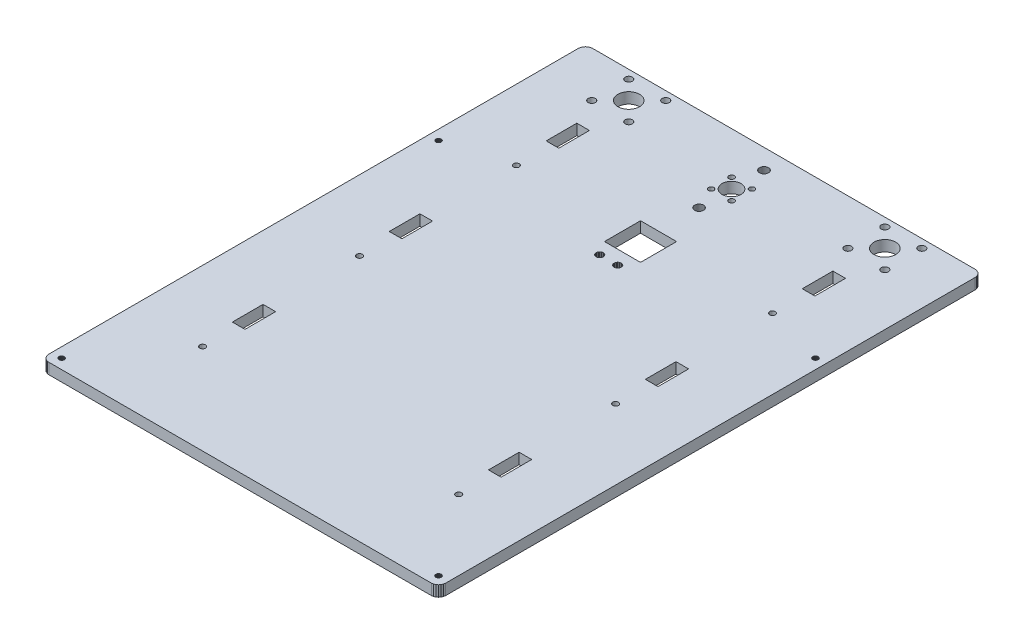
SolidWorks part; units mm, degrees
ref_plane "Alzado" through (0, 0, 0) normal (0, 0, 1) x (1, 0, 0)
ref_plane "Planta" through (0, 0, 0) normal (0, 1, 0) x (1, 0, 0)
ref_plane "Vista lateral" through (0, 0, 0) normal (1, 0, 0) x (0, 0, -1)
sketch "Croquis1" plane through (0, 0, 0) normal (0, 1, 0) x (1, 0, 0)
  line L0 (-2.4786, 139.4098) -> (-2.5, 139.7361)
  line L1 (-2.4148, 139.0891) -> (-2.4786, 139.4098)
  line L2 (-2.3097, 138.7794) -> (-2.4148, 139.0891)
  line L3 (-2.1651, 138.4861) -> (-2.3097, 138.7794)
  line L4 (-1.9834, 138.2142) -> (-2.1651, 138.4861)
  line L5 (-1.7678, 137.9684) -> (-1.9834, 138.2142)
  line L6 (-1.5219, 137.7528) -> (-1.7678, 137.9684)
  line L7 (-1.25, 137.5711) -> (-1.5219, 137.7528)
  line L8 (-0.9567, 137.4264) -> (-1.25, 137.5711)
  line L9 (-0.647, 137.3213) -> (-0.9567, 137.4264)
  line L10 (-0.3263, 137.2575) -> (-0.647, 137.3213)
  line L11 (0, 137.2361) -> (-0.3263, 137.2575)
  line L12 (0.3263, 137.2575) -> (0, 137.2361)
  line L13 (0.647, 137.3213) -> (0.3263, 137.2575)
  line L14 (0.9567, 137.4264) -> (0.647, 137.3213)
  line L15 (1.25, 137.5711) -> (0.9567, 137.4264)
  line L16 (1.5219, 137.7528) -> (1.25, 137.5711)
  line L17 (1.7678, 137.9684) -> (1.5219, 137.7528)
  line L18 (1.9834, 138.2142) -> (1.7678, 137.9684)
  line L19 (2.1651, 138.4861) -> (1.9834, 138.2142)
  line L20 (2.3097, 138.7794) -> (2.1651, 138.4861)
  line L21 (2.4148, 139.0891) -> (2.3097, 138.7794)
  line L22 (2.4786, 139.4098) -> (2.4148, 139.0891)
  line L23 (2.5, 139.7361) -> (2.4786, 139.4098)
  line L24 (-2.4148, 103.0891) -> (-2.4786, 103.4098)
  line L25 (-2.3097, 102.7794) -> (-2.4148, 103.0891)
  line L26 (-2.1651, 102.4861) -> (-2.3097, 102.7794)
  line L27 (-9, 81.2639) -> (9, 81.2639)
  line L28 (-2.4786, 103.4098) -> (-2.5, 103.7361)
  line L29 (-1.9834, 102.2142) -> (-2.1651, 102.4861)
  line L30 (-1.7678, 101.9684) -> (-1.9834, 102.2142)
  line L31 (-1.5219, 101.7528) -> (-1.7678, 101.9684)
  line L32 (-1.25, 101.5711) -> (-1.5219, 101.7528)
  line L33 (-0.9567, 101.4264) -> (-1.25, 101.5711)
  line L34 (-0.647, 101.3213) -> (-0.9567, 101.4264)
  line L35 (-0.3263, 101.2575) -> (-0.647, 101.3213)
  line L36 (0, 101.2361) -> (-0.3263, 101.2575)
  line L37 (0.3263, 101.2575) -> (0, 101.2361)
  line L38 (0.647, 101.3213) -> (0.3263, 101.2575)
  line L39 (0.9567, 101.4264) -> (0.647, 101.3213)
  line L40 (1.25, 101.5711) -> (0.9567, 101.4264)
  line L41 (1.5219, 101.7528) -> (1.25, 101.5711)
  line L42 (1.7678, 101.9684) -> (1.5219, 101.7528)
  line L43 (1.9834, 102.2142) -> (1.7678, 101.9684)
  line L44 (2.1651, 102.4861) -> (1.9834, 102.2142)
  line L45 (2.3097, 102.7794) -> (2.1651, 102.4861)
  line L46 (2.4148, 103.0891) -> (2.3097, 102.7794)
  line L47 (2.4786, 103.4098) -> (2.4148, 103.0891)
  line L48 (2.5, 103.7361) -> (2.4786, 103.4098)
  line L50 (3.0681, 53.0893) -> (3, 53.6069)
  line L51 (3.2679, 52.6069) -> (3.0681, 53.0893)
  line L52 (3.5858, 52.1927) -> (3.2679, 52.6069)
  line L53 (4, 51.8749) -> (3.5858, 52.1927)
  line L54 (4.4824, 51.6751) -> (4, 51.8749)
  line L55 (5, 51.6069) -> (4.4824, 51.6751)
  line L56 (5.5176, 51.6751) -> (5, 51.6069)
  line L58 (6, 51.8749) -> (5.5176, 51.6751)
  line L59 (6.4142, 52.1927) -> (6, 51.8749)
  line L60 (6.7321, 52.6069) -> (6.4142, 52.1927)
  line L61 (6.9319, 53.0893) -> (6.7321, 52.6069)
  line L62 (7, 53.6069) -> (6.9319, 53.0893)
  line L63 (-105.9489, -145.6244) -> (-106, -145.2361)
  line L64 (-105.799, -145.9861) -> (-105.9489, -145.6244)
  line L65 (-105.5607, -146.2968) -> (-105.799, -145.9861)
  line L66 (-105.25, -146.5352) -> (-105.5607, -146.2968)
  line L67 (-104.8882, -146.685) -> (-105.25, -146.5352)
  line L68 (-104.5, -146.7361) -> (-104.8882, -146.685)
  line L69 (-106, -150.7361) -> (106, -150.7361)
  line L70 (-104.1118, -146.685) -> (-104.5, -146.7361)
  line L71 (-103.75, -146.5352) -> (-104.1118, -146.685)
  line L72 (-103.4393, -146.2968) -> (-103.75, -146.5352)
  line L73 (-103.201, -145.9861) -> (-103.4393, -146.2968)
  line L74 (-103.0511, -145.6244) -> (-103.201, -145.9861)
  line L75 (-103, -145.2361) -> (-103.0511, -145.6244)
  line L77 (60.747, 148.0892) -> (60.747, 143.8892) construction
  line L78 (-71, 135.7361) -> (-71, -150.7361) construction
  line L79 (71, 135.7361) -> (71, -150.7361) construction
  line L80 (-74.5, 23.4409) -> (-67.5, 23.4409)
  line L81 (-74.5, 110.4409) -> (-67.5, 110.4409)
  line L82 (-74.5, 110.4409) -> (-74.5, 93.4409)
  line L83 (-74.5, 93.4409) -> (-67.5, 93.4409)
  line L84 (-67.5, 110.4409) -> (-67.5, 93.4409)
  line L85 (-74.5, 110.4409) -> (-67.5, 93.4409) construction
  line L86 (-74.5, 93.4409) -> (-67.5, 110.4409) construction
  line L87 (-74.5, 23.4409) -> (-74.5, 6.4409)
  line L88 (-74.5, 6.4409) -> (-67.5, 6.4409)
  line L89 (-67.5, 23.4409) -> (-67.5, 6.4409)
  line L90 (-74.5, 23.4409) -> (-67.5, 6.4409) construction
  line L91 (-74.5, 6.4409) -> (-67.5, 23.4409) construction
  line L92 (-74.5, -63.5591) -> (-67.5, -63.5591)
  line L93 (-74.5, -63.5591) -> (-74.5, -80.5591)
  line L94 (-74.5, -80.5591) -> (-67.5, -80.5591)
  line L95 (-67.5, -63.5591) -> (-67.5, -80.5591)
  line L96 (-74.5, -63.5591) -> (-67.5, -80.5591) construction
  line L97 (-74.5, -80.5591) -> (-67.5, -63.5591) construction
  line L98 (0, 121.7361) -> (0, -150.7361) construction
  line L100 (74.5, -80.5591) -> (67.5, -63.5591) construction
  line L101 (74.5, -63.5591) -> (67.5, -80.5591) construction
  line L102 (74.5, 6.4409) -> (67.5, 23.4409) construction
  line L103 (74.5, 23.4409) -> (67.5, 6.4409) construction
  line L104 (74.5, 93.4409) -> (67.5, 110.4409) construction
  line L105 (74.5, 110.4409) -> (67.5, 93.4409) construction
  line L106 (67.5, -63.5591) -> (67.5, -80.5591)
  line L107 (74.5, -80.5591) -> (67.5, -80.5591)
  line L108 (74.5, -63.5591) -> (74.5, -80.5591)
  line L109 (74.5, -63.5591) -> (67.5, -63.5591)
  line L110 (67.5, 23.4409) -> (67.5, 6.4409)
  line L111 (74.5, 6.4409) -> (67.5, 6.4409)
  line L112 (74.5, 23.4409) -> (74.5, 6.4409)
  line L113 (67.5, 110.4409) -> (67.5, 93.4409)
  line L114 (74.5, 93.4409) -> (67.5, 93.4409)
  line L115 (74.5, 110.4409) -> (74.5, 93.4409)
  line L116 (74.5, 110.4409) -> (67.5, 110.4409)
  line L117 (74.5, 23.4409) -> (67.5, 23.4409)
  line L150 (10, 62.2639) -> (10, 61.2639)
  line L151 (103.201, -145.9861) -> (103.0511, -145.6244)
  line L152 (10, 80.2639) -> (10, 62.2639)
  line L189 (103.0511, -145.6244) -> (103, -145.2361)
  line L244 (103.4393, -146.2968) -> (103.201, -145.9861)
  line L245 (103.75, -146.5352) -> (103.4393, -146.2968)
  line L246 (104.1118, -146.685) -> (103.75, -146.5352)
  line L247 (104.5, -146.7361) -> (104.1118, -146.685)
  line L248 (104.8882, -146.685) -> (104.5, -146.7361)
  line L249 (105.25, -146.5352) -> (104.8882, -146.685)
  line L250 (105.5607, -146.2968) -> (105.25, -146.5352)
  line L251 (105.799, -145.9861) -> (105.5607, -146.2968)
  line L252 (105.9489, -145.6244) -> (105.799, -145.9861)
  line L253 (106, -145.2361) -> (105.9489, -145.6244)
  line L254 (106, -150.7361) -> (107.0353, -150.5998)
  line L255 (107.0353, 150.5998) -> (106, 150.7361)
  line L256 (107.0353, -150.5998) -> (108, -150.2002)
  line L257 (108, 150.2002) -> (107.0353, 150.5998)
  line L258 (108, -150.2002) -> (108.8284, -149.5646)
  line L259 (108.8284, 149.5646) -> (108, 150.2002)
  line L260 (108.8284, -149.5646) -> (109.4641, -148.7361)
  line L261 (109.4641, 148.7361) -> (108.8284, 149.5646)
  line L262 (109.4641, -148.7361) -> (109.8637, -147.7714)
  line L263 (109.8637, 147.7714) -> (109.4641, 148.7361)
  line L264 (109.8637, -147.7714) -> (110, -146.7361)
  line L265 (110, -146.7361) -> (110, 146.7361)
  line L266 (110, 146.7361) -> (109.8637, 147.7714)
  line L267 (-110, 146.7361) -> (-110, -146.7361)
  line L268 (-110, -146.7361) -> (-109.8637, -147.7714)
  line L269 (-109.8637, 147.7714) -> (-110, 146.7361)
  line L270 (-109.8637, -147.7714) -> (-109.4641, -148.7361)
  line L271 (-109.4641, 148.7361) -> (-109.8637, 147.7714)
  line L272 (-109.4641, -148.7361) -> (-108.8284, -149.5646)
  line L273 (-108.8284, 149.5646) -> (-109.4641, 148.7361)
  line L274 (-108.8284, -149.5646) -> (-108, -150.2002)
  line L275 (-108, 150.2002) -> (-108.8284, 149.5646)
  line L276 (-108, -150.2002) -> (-107.0353, -150.5998)
  line L277 (-107.0353, 150.5998) -> (-108, 150.2002)
  line L278 (-107.0353, -150.5998) -> (-106, -150.7361)
  line L279 (-106, 150.7361) -> (-107.0353, 150.5998)
  line L280 (-106, 63.7639) -> (-105.9489, 64.1521)
  line L291 (106, 150.7361) -> (-106, 150.7361)
  line L292 (-105.9489, 64.1521) -> (-105.799, 64.5139)
  line L293 (-105.799, 64.5139) -> (-105.5607, 64.8245)
  line L294 (-105.5607, 64.8245) -> (-105.25, 65.0629)
  line L295 (-105.25, 65.0629) -> (-104.8882, 65.2128)
  line L296 (-104.8882, 65.2128) -> (-104.5, 65.2639)
  line L297 (-104.5, 65.2639) -> (-104.1118, 65.2128)
  line L298 (-104.1118, 65.2128) -> (-103.75, 65.0629)
  line L299 (-103.75, 65.0629) -> (-103.4393, 64.8245)
  line L300 (-103.4393, 64.8245) -> (-103.201, 64.5139)
  line L301 (-103.201, 64.5139) -> (-103.0511, 64.1521)
  line L302 (-103.0511, 64.1521) -> (-103, 63.7639)
  line L358 (-0.647, 142.151) -> (-0.3263, 142.2147)
  line L359 (-0.9567, 142.0458) -> (-0.647, 142.151)
  line L360 (-1.25, 141.9012) -> (-0.9567, 142.0458)
  line L361 (-1.5219, 141.7195) -> (-1.25, 141.9012)
  line L362 (-1.7678, 141.5039) -> (-1.5219, 141.7195)
  line L363 (-1.9834, 141.258) -> (-1.7678, 141.5039)
  line L364 (-2.1651, 140.9861) -> (-1.9834, 141.258)
  line L365 (-2.3097, 140.6928) -> (-2.1651, 140.9861)
  line L366 (-2.4148, 140.3832) -> (-2.3097, 140.6928)
  line L367 (-2.4786, 140.0625) -> (-2.4148, 140.3832)
  line L368 (-10, 61.2639) -> (-10, 62.2639)
  line L369 (-10, 81.2639) -> (-9, 81.2639)
  line L370 (-2.5, 139.7361) -> (-2.4786, 140.0625)
  line L371 (-0.3263, 142.2147) -> (0, 142.2361)
  line L372 (0, 142.2361) -> (0.3263, 142.2147)
  line L373 (0.3263, 142.2147) -> (0.647, 142.151)
  line L374 (0.647, 142.151) -> (0.9567, 142.0458)
  line L375 (0.9567, 142.0458) -> (1.25, 141.9012)
  line L376 (1.25, 141.9012) -> (1.5219, 141.7195)
  line L377 (1.5219, 141.7195) -> (1.7678, 141.5039)
  line L378 (1.7678, 141.5039) -> (1.9834, 141.258)
  line L379 (1.9834, 141.258) -> (2.1651, 140.9861)
  line L380 (2.1651, 140.9861) -> (2.3097, 140.6928)
  line L381 (2.3097, 140.6928) -> (2.4148, 140.3832)
  line L382 (2.4148, 140.3832) -> (2.4786, 140.0625)
  line L383 (2.4786, 140.0625) -> (2.5, 139.7361)
  line L386 (9, 81.2639) -> (10, 81.2639)
  line L387 (10, 81.2639) -> (10, 80.2639)
  line L476 (103, 63.7639) -> (103.0511, 64.1521)
  line L477 (103.0511, 64.1521) -> (103.201, 64.5139)
  line L478 (103.201, 64.5139) -> (103.4393, 64.8245)
  line L479 (103.4393, 64.8245) -> (103.75, 65.0629)
  line L480 (103.75, 65.0629) -> (104.1118, 65.2128)
  line L481 (104.1118, 65.2128) -> (104.5, 65.2639)
  line L482 (104.5, 65.2639) -> (104.8882, 65.2128)
  line L483 (104.8882, 65.2128) -> (105.25, 65.0629)
  line L484 (105.25, 65.0629) -> (105.5607, 64.8245)
  line L485 (105.5607, 64.8245) -> (105.799, 64.5139)
  line L486 (105.799, 64.5139) -> (105.9489, 64.1521)
  line L487 (105.9489, 64.1521) -> (106, 63.7639)
  line L488 (103, -145.2361) -> (103.0511, -144.8479)
  line L489 (103.0511, 63.3756) -> (103, 63.7639)
  line L490 (103.0511, -144.8479) -> (103.201, -144.4861)
  line L491 (103.201, 63.0139) -> (103.0511, 63.3756)
  line L492 (103.201, -144.4861) -> (103.4393, -144.1755)
  line L493 (103.4393, 62.7032) -> (103.201, 63.0139)
  line L494 (103.4393, -144.1755) -> (103.75, -143.9371)
  line L495 (103.75, 62.4648) -> (103.4393, 62.7032)
  line L496 (103.75, -143.9371) -> (104.1118, -143.7872)
  line L497 (104.1118, 62.315) -> (103.75, 62.4648)
  line L498 (104.1118, -143.7872) -> (104.5, -143.7361)
  line L499 (104.5, 62.2639) -> (104.1118, 62.315)
  line L500 (104.5, -143.7361) -> (104.8882, -143.7872)
  line L501 (104.8882, 62.315) -> (104.5, 62.2639)
  line L502 (104.8882, -143.7872) -> (105.25, -143.9371)
  line L503 (105.25, 62.4648) -> (104.8882, 62.315)
  line L504 (105.25, -143.9371) -> (105.5607, -144.1755)
  line L505 (105.5607, 62.7032) -> (105.25, 62.4648)
  line L506 (105.5607, -144.1755) -> (105.799, -144.4861)
  line L507 (105.799, 63.0139) -> (105.5607, 62.7032)
  line L508 (105.799, -144.4861) -> (105.9489, -144.8479)
  line L509 (105.9489, 63.3756) -> (105.799, 63.0139)
  line L510 (105.9489, -144.8479) -> (106, -145.2361)
  line L511 (106, 63.7639) -> (105.9489, 63.3756)
  line L622 (-9, 61.2639) -> (-10, 61.2639)
  line L624 (-7, 53.6069) -> (-6.9319, 54.1246)
  line L625 (-6.9319, 54.1246) -> (-6.7321, 54.6069)
  line L626 (-6.7321, 54.6069) -> (-6.4142, 55.0211)
  line L627 (-6.4142, 55.0211) -> (-6, 55.339)
  line L628 (-6, 55.339) -> (-5.5176, 55.5388)
  line L629 (9, 61.2639) -> (-9, 61.2639)
  line L631 (-5.5176, 55.5388) -> (-5, 55.6069)
  line L632 (-5, 55.6069) -> (-4.4824, 55.5388)
  line L633 (-4.4824, 55.5388) -> (-4, 55.339)
  line L634 (-4, 55.339) -> (-3.5858, 55.0211)
  line L635 (-3.5858, 55.0211) -> (-3.2679, 54.6069)
  line L636 (-3.2679, 54.6069) -> (-3.0681, 54.1246)
  line L637 (-3.0681, 54.1246) -> (-3, 53.6069)
  line L638 (3.2679, 54.6069) -> (3.5858, 55.0211)
  line L639 (3.0681, 54.1246) -> (3.2679, 54.6069)
  line L640 (3, 53.6069) -> (3.0681, 54.1246)
  line L643 (3.5858, 55.0211) -> (4, 55.339)
  line L644 (4, 55.339) -> (4.4824, 55.5388)
  line L645 (4.4824, 55.5388) -> (5, 55.6069)
  line L646 (5, 55.6069) -> (5.5176, 55.5388)
  line L647 (5.5176, 55.5388) -> (6, 55.339)
  line L648 (6, 55.339) -> (6.4142, 55.0211)
  line L649 (6.4142, 55.0211) -> (6.7321, 54.6069)
  line L650 (6.7321, 54.6069) -> (6.9319, 54.1246)
  line L651 (6.9319, 54.1246) -> (7, 53.6069)
  line L654 (10, 61.2639) -> (9, 61.2639)
  line L656 (-2.5, 103.7361) -> (-2.4786, 104.0625)
  line L657 (-2.4786, 104.0625) -> (-2.4148, 104.3832)
  line L658 (-2.4148, 104.3832) -> (-2.3097, 104.6928)
  line L659 (-2.3097, 104.6928) -> (-2.1651, 104.9861)
  line L660 (-2.1651, 104.9861) -> (-1.9834, 105.258)
  line L661 (-1.9834, 105.258) -> (-1.7678, 105.5039)
  line L662 (-1.7678, 105.5039) -> (-1.5219, 105.7195)
  line L663 (-1.5219, 105.7195) -> (-1.25, 105.9012)
  line L664 (-1.25, 105.9012) -> (-0.9567, 106.0458)
  line L665 (-0.9567, 106.0458) -> (-0.647, 106.151)
  line L666 (-0.647, 106.151) -> (-0.3263, 106.2147)
  line L667 (-0.3263, 106.2147) -> (0, 106.2361)
  line L668 (0, 106.2361) -> (0.3263, 106.2147)
  line L669 (0.3263, 106.2147) -> (0.647, 106.151)
  line L670 (0.647, 106.151) -> (0.9567, 106.0458)
  line L671 (0.9567, 106.0458) -> (1.25, 105.9012)
  line L672 (1.25, 105.9012) -> (1.5219, 105.7195)
  line L673 (1.5219, 105.7195) -> (1.7678, 105.5039)
  line L674 (1.7678, 105.5039) -> (1.9834, 105.258)
  line L675 (1.9834, 105.258) -> (2.1651, 104.9861)
  line L676 (2.1651, 104.9861) -> (2.3097, 104.6928)
  line L677 (2.3097, 104.6928) -> (2.4148, 104.3832)
  line L678 (2.4148, 104.3832) -> (2.4786, 104.0625)
  line L679 (2.4786, 104.0625) -> (2.5, 103.7361)
  line L680 (-10, 80.2639) -> (-10, 81.2639)
  line L681 (-10, 62.2639) -> (-10, 80.2639)
  line L683 (-6.9319, 53.0893) -> (-7, 53.6069)
  line L684 (-6.7321, 52.6069) -> (-6.9319, 53.0893)
  line L685 (-6.4142, 52.1927) -> (-6.7321, 52.6069)
  line L686 (-6, 51.8749) -> (-6.4142, 52.1927)
  line L687 (-5.5176, 51.6751) -> (-6, 51.8749)
  line L688 (-5, 51.6069) -> (-5.5176, 51.6751)
  line L689 (-4.4824, 51.6751) -> (-5, 51.6069)
  line L691 (-4, 51.8749) -> (-4.4824, 51.6751)
  line L692 (-3.5858, 52.1927) -> (-4, 51.8749)
  line L693 (-3.2679, 52.6069) -> (-3.5858, 52.1927)
  line L694 (-3.0681, 53.0893) -> (-3.2679, 52.6069)
  line L695 (-3, 53.6069) -> (-3.0681, 53.0893)
  line L798 (-106, -145.2361) -> (-105.9489, -144.8479)
  line L799 (-105.9489, 63.3756) -> (-106, 63.7639)
  line L800 (-105.9489, -144.8479) -> (-105.799, -144.4861)
  line L801 (-105.799, 63.0139) -> (-105.9489, 63.3756)
  line L802 (-105.799, -144.4861) -> (-105.5607, -144.1755)
  line L803 (-105.5607, 62.7032) -> (-105.799, 63.0139)
  line L804 (-105.5607, -144.1755) -> (-105.25, -143.9371)
  line L805 (-105.25, 62.4648) -> (-105.5607, 62.7032)
  line L806 (-105.25, -143.9371) -> (-104.8882, -143.7872)
  line L807 (-104.8882, 62.315) -> (-105.25, 62.4648)
  line L808 (-104.8882, -143.7872) -> (-104.5, -143.7361)
  line L809 (-104.5, 62.2639) -> (-104.8882, 62.315)
  line L810 (-104.5, -143.7361) -> (-104.1118, -143.7872)
  line L811 (-104.1118, 62.315) -> (-104.5, 62.2639)
  line L812 (-104.1118, -143.7872) -> (-103.75, -143.9371)
  line L813 (-103.75, 62.4648) -> (-104.1118, 62.315)
  line L814 (-103.75, -143.9371) -> (-103.4393, -144.1755)
  line L815 (-103.4393, 62.7032) -> (-103.75, 62.4648)
  line L816 (-103.4393, -144.1755) -> (-103.201, -144.4861)
  line L817 (-103.201, 63.0139) -> (-103.4393, 62.7032)
  line L818 (-103.201, -144.4861) -> (-103.0511, -144.8479)
  line L819 (-103.0511, 63.3756) -> (-103.201, 63.0139)
  line L820 (-103.0511, -144.8479) -> (-103, -145.2361)
  line L821 (-103, 63.7639) -> (-103.0511, 63.3756)
  line L822 (-8.3, 113.4361) -> (8.3, 130.0361) construction
  line L823 (-8.3, 130.0361) -> (8.3, 113.4361) construction
  line L824 (-81.253, 148.0892) -> (-81.253, 143.8892) construction
  circle A0 centre (0, 121.7361) radius 5.25
  circle A1 centre (5.6569, 127.393) radius 1.5
  circle A2 centre (-5.6569, 127.393) radius 1.5
  circle A3 centre (-5.6569, 116.0793) radius 1.5
  circle A4 centre (5.6569, 116.0793) radius 1.5
  circle A5 centre (-81.253, 145.9892) radius 2
  circle A6 centre (-60.747, 145.9892) radius 2
  circle A7 centre (-81.253, 125.4831) radius 2
  circle A8 centre (-60.747, 125.4831) radius 2
  circle A9 centre (-71, 135.7361) radius 6
  circle A10 centre (60.747, 145.9892) radius 2
  circle A11 centre (81.253, 145.9892) radius 2
  circle A12 centre (60.747, 125.4831) radius 2
  circle A13 centre (81.253, 125.4831) radius 2
  circle A14 centre (60.747, 145.9892) radius 2
  circle A15 centre (81.253, 145.9892) radius 2
  circle A16 centre (60.747, 125.4831) radius 2
  circle A17 centre (81.253, 125.4831) radius 2
  circle A18 centre (71, 135.7361) radius 6
  circle A19 centre (-71, 73.4409) radius 1.6
  circle A20 centre (-71, -13.5591) radius 1.6
  circle A21 centre (-71, -100.5591) radius 1.6
  circle A22 centre (71, -100.5591) radius 1.6
  circle A23 centre (71, -13.5591) radius 1.6
  circle A24 centre (71, 73.4409) radius 1.6
  point P110 (-71, 110.4409)
  point P113 (-71, -145.2361)
  point P114 (-71, 101.9409)
  point P121 (-71, 23.4409)
  point P122 (-71, 14.9409)
  point P129 (-71, -63.5591)
  point P130 (-71, -63.5591)
  point P131 (-71, -72.0591)
  point P172 (71, -72.0591)
  point P173 (71, -63.5591)
  point P174 (71, 14.9409)
  point P175 (71, 23.4409)
  point P176 (71, 101.9409)
  point P177 (71, 110.4409)
  dimension "D2" = 4
  dimension "D3" = 4
  dimension "D4" = 4
  dimension "D5" = 12
  dimension "D6" = 4
  dimension "D7" = 4
  dimension "D8" = 4
  dimension "D9" = 4
  dimension "D10" = 4
  dimension "D11" = 4
  dimension "D12" = 4
  dimension "D13" = 12
  dimension "D14" = 17
  dimension "D1" = 11.3137
  dimension "D15" = 7
  dimension "D16" = 20
  dimension "D17" = 17
  dimension "D18" = 17
extrude "Saliente-Extruir1" add sketch "Croquis1" along normal blind 6 contours L255 L291 L279 L277 L275 L273 L271 L269 L267 L268 L270 L272 L274 L276 L278 L69 L254 L256 L258 L260 L262 L264 L265 L266 L263 L261 L259 L257 A23 L302 L821 L819 L817 L815 L813 L811 L809 L807 L805 L803 L801 L799 L280 L292 L293 L294 L295 L296 L297
